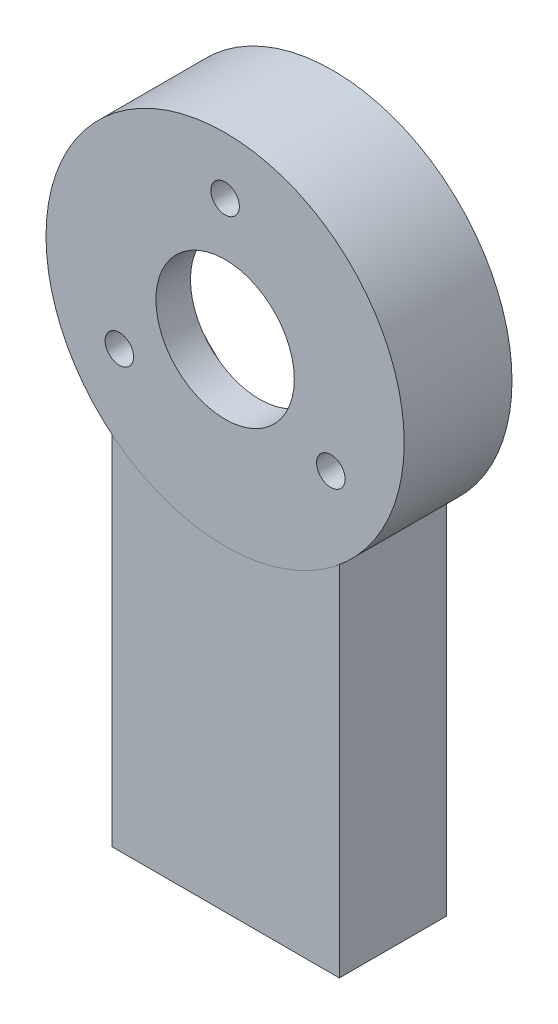
SolidWorks part; units mm, degrees
ref_plane "Front Plane" through (0, 0, 0) normal (0, 0, 1) x (1, 0, 0)
ref_plane "Top Plane" through (0, 0, 0) normal (0, 1, 0) x (1, 0, 0)
ref_plane "Right Plane" through (0, 0, 0) normal (1, 0, 0) x (0, 0, -1)
other "Bounding Box"
ref_plane "Default Plane" through (22, -59, -3.2424) normal (-1, 0, 0) x (0, 0, 1)
sketch "Sketch1" plane through (0, 0, 0) normal (0, 0, 1) x (1, 0, 0)
  line L0 (0, 0) -> (0, 22) construction
  circle A0 centre (0, 0) radius 22
  circle A1 centre (0, 15) radius 1.75
  circle A2 centre (12.9904, -7.5) radius 1.75
  circle A3 centre (-12.9904, -7.5) radius 1.75
  circle A4 centre (0, 0) radius 8.5
  point P13 (0, 0)
  dimension "D1" = 44
  dimension "D2" = 3.5
  dimension "D4" = 17
  dimension "D3" = 3
extrude "Boss-Extrude1" add sketch "Sketch1" along normal blind 10 and the other way blind 3.2424
sketch "Sketch2" plane through (0, 0, -3.2424) normal (0, 0, -1) x (-1, 0, 0)
  line L0 (-13.9536, -17.0088) -> (13.9536, -17.0088)
  line L1 (-13.9536, -17.0088) -> (-13.9536, -61)
  line L2 (13.9536, -17.0088) -> (13.9536, -61)
  line L3 (-13.9536, -61) -> (13.9536, -61)
  line L4 (0, 0) -> (0, 22) construction
  circle A0 centre (0, 0) radius 22 construction
  dimension "D1" = 61
extrude "Boss-Extrude3" add sketch "Sketch2" against normal blind 13.1605
sketch "Sketch3" plane through (0, 0, -3.2424) normal (0, 0, -1) x (-1, 0, 0)
  circle A0 centre (0, 0) radius 21.15
  dimension "D1" = 42.3
extrude "Cut-Extrude1" cut sketch "Sketch3" against normal blind 9
sketch "Sketch4" plane through (0, 0, 10) normal (0, 0, 1) x (1, 0, 0)
  line L0 (0, 0) -> (0, 3.0461) construction
  circle A1 centre (0, 15) radius 1.75 construction
  point P5 (0, 0)
  dimension "D1" = 15
